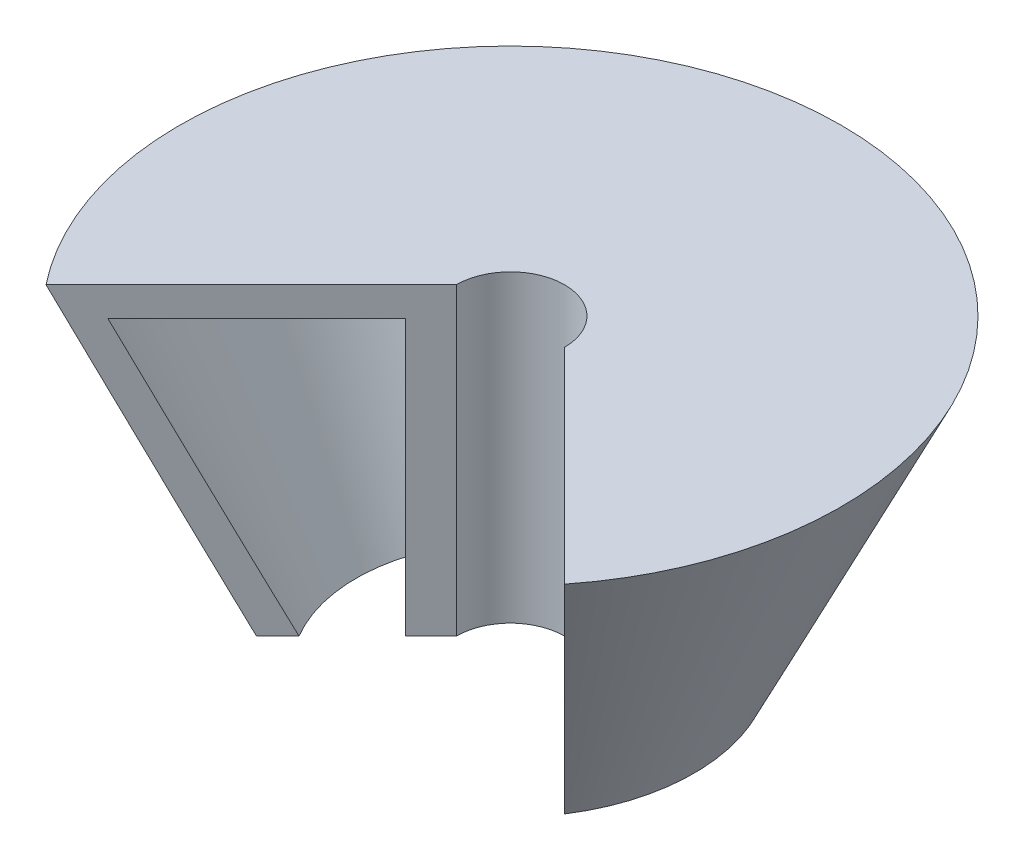
SolidWorks part; units mm, degrees
ref_plane "Alzado" through (0, 0, 0) normal (0, 0, 1) x (1, 0, 0)
ref_plane "Planta" through (0, 0, 0) normal (0, 1, 0) x (1, 0, 0)
ref_plane "Vista lateral" through (0, 0, 0) normal (1, 0, 0) x (0, 0, -1)
sketch "Croquis1" plane through (0, 0, 0) normal (0, 0, 1) x (1, 0, 0)
  line L0 (-78.0064, 33.573) -> (-78.0064, -45.2805) construction
  line L1 (-79.8564, 4.5463) -> (-80.8564, 4.5463) construction
  line L2 (-84.2814, -5.8537) -> (-84.2814, 4.5463) construction
  line L3 (-80.8564, 4.5463) -> (-80.8564, 3.5463) construction
  line L4 (-89.3064, 4.5463) -> (-84.2814, -5.8537)
  line L5 (-80.8564, 3.5463) -> (-80.8564, -5.8537)
  line L6 (-80.8564, 3.5463) -> (-87.8224, 3.5463)
  line L7 (-79.8564, 4.5463) -> (-79.8564, -5.8537)
  line L8 (-80.8564, -5.8537) -> (-79.8564, -5.8537)
  line L9 (-89.3064, 4.5463) -> (-79.8564, 4.5463)
  line L10 (-87.8224, 3.5463) -> (-83.2805, -5.8537)
  line L11 (-83.2805, -5.8537) -> (-84.2814, -5.8537)
  dimension "D2" = 1
revolve "Revolución1" add sketch "Croquis1" angle 360 about L0
sketch "Croquis2" plane through (0, 4.5463, 0) normal (0, 1, 0) x (1, 0, 0)
  line L0 (-76.1564, 0) -> (-69.1448, -7.0116)
  line L1 (-79.8564, 0) -> (-86.868, -7.0116)
  circle A2 centre (-78.0064, 0) radius 1.85 construction
  circle A3 centre (-78.0064, 0) radius 11.3 construction
  arc A4 (-79.8564, 0) -> (-76.1564, 0) centre (-78.0064, 0) ccw
  arc A5 (-86.868, -7.0116) -> (-69.1448, -7.0116) centre (-78.0064, 0) ccw
extrude "Cortar-Extruir1" cut sketch "Croquis2" against normal blind 11
